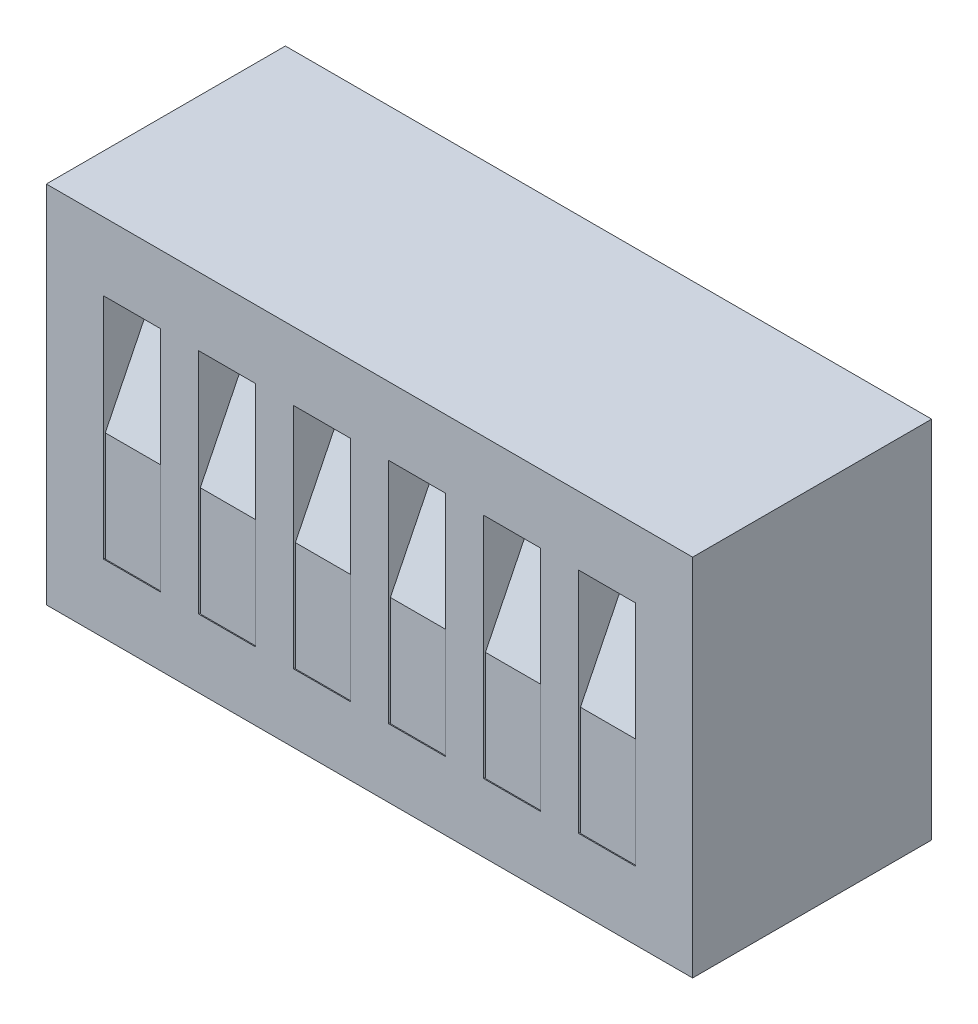
SolidWorks part; units mm, degrees
ref_plane "Front Plane" through (0, 0, 0) normal (0, 0, 1) x (1, 0, 0)
ref_plane "Top Plane" through (0, 0, 0) normal (0, 1, 0) x (1, 0, 0)
ref_plane "Right Plane" through (0, 0, 0) normal (1, 0, 0) x (0, 0, -1)
ref_plane "Plane1" through (0, 0, 6.3881) normal (0, 0, 1) x (1, 0, 0)
sketch "Sketch1" plane through (0, 0, 6.3881) normal (0, 0, 1) x (1, 0, 0)
  line L0 (17.272, 0) -> (17.272, 9.7409)
  line L1 (17.272, 9.7409) -> (0, 9.7409)
  line L2 (0, 9.7409) -> (0, 0)
  line L3 (0, 0) -> (17.272, 0)
extrude "Boss-Extrude1" add sketch "Sketch1" against normal blind 6.3881
sketch "Sketch2" plane through (0, 0, 6.3881) normal (0, 0, 1) x (1, 0, 0)
  line L0 (1.524, 1.8224) -> (3.048, 1.8224)
  line L1 (3.048, 1.8224) -> (3.048, 7.9185)
  line L2 (3.048, 7.9185) -> (1.524, 7.9185)
  line L3 (1.524, 7.9185) -> (1.524, 1.8224)
extrude "Cut-Extrude1" cut sketch "Sketch2" against normal blind 2.54
pattern_linear "LPattern1" count 6 spacing 2.54 along (1, 0, 0) of "Cut-Extrude1"
ref_plane "Plane2" through (3.0226, 0, 0) normal (1, 0, 0) x (0, 0, -1)
sketch "Sketch3" plane through (3.0226, 0, 0) normal (1, 0, 0) x (0, 0, -1)
  line L0 (-6.3627, 1.8224) -> (-3.8481, 1.8224)
  line L1 (-3.8481, 1.8224) -> (-3.8481, 7.9185)
  line L2 (-3.8481, 7.9185) -> (-4.8006, 7.9185)
  line L3 (-4.8006, 7.9185) -> (-6.3627, 4.7435)
  line L4 (-6.3627, 4.7435) -> (-6.3627, 1.8224)
extrude "Boss-Extrude2" add sketch "Sketch3" against normal blind 1.4732
pattern_linear "LPattern2" count 6 spacing 2.54 along (1, 0, 0) of "Boss-Extrude2"
